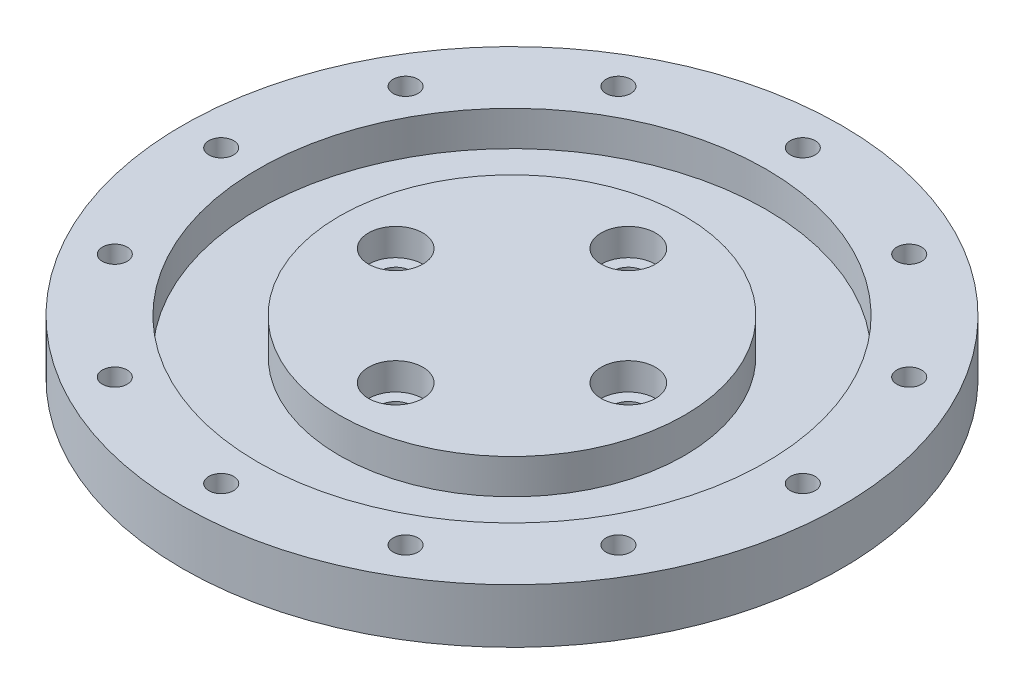
SolidWorks part; units mm, degrees
ref_plane "Ön Düzlem" through (0, 0, 0) normal (0, 0, 1) x (1, 0, 0)
ref_plane "Üst Düzlem" through (0, 0, 0) normal (0, 1, 0) x (1, 0, 0)
ref_plane "Sağ Düzlem" through (0, 0, 0) normal (1, 0, 0) x (0, 0, -1)
sketch "Sketch1" plane through (0, 0, 0) normal (0, 1, 0) x (1, 0, 0)
  circle A0 centre (0, 0) radius 42.5
  dimension "D1" = 85
extrude "Boss-Extrude1" add sketch "Sketch1" along normal blind 7
sketch "Sketch2" plane through (0, 7, 0) normal (0, 1, 0) x (1, 0, 0)
  circle A0 centre (0, 0) radius 22.25
  circle A1 centre (0, 0) radius 32.75
  dimension "D1" = 44.5
  dimension "D2" = 65.5
extrude "Cut-Extrude1" cut sketch "Sketch2" against normal blind 4.5
sketch "Sketch3" plane through (0, 7, 0) normal (0, 1, 0) x (1, 0, 0)
  circle A0 centre (0, 37.5) radius 1.6
  circle A1 centre (18.75, 32.476) radius 1.6
  circle A2 centre (32.476, 18.75) radius 1.6
  circle A3 centre (37.5, 0) radius 1.6
  circle A4 centre (32.476, -18.75) radius 1.6
  circle A5 centre (18.75, -32.476) radius 1.6
  circle A6 centre (0, -37.5) radius 1.6
  circle A7 centre (-18.75, -32.476) radius 1.6
  circle A8 centre (-32.476, -18.75) radius 1.6
  circle A9 centre (-37.5, 0) radius 1.6
  circle A10 centre (-32.476, 18.75) radius 1.6
  circle A11 centre (-18.75, 32.476) radius 1.6
  dimension "D1" = 37.5
  dimension "D2" = 12
extrude "Cut-Extrude2" cut sketch "Sketch3" against normal through all
sketch "Sketch4" plane through (0, 7, 0) normal (0, 1, 0) x (1, 0, 0)
  circle A0 centre (0, 15) radius 2
  circle A1 centre (15, 0) radius 2
  circle A2 centre (0, -15) radius 2
  circle A3 centre (-15, 0) radius 2
  dimension "D1" = 4
  dimension "D2" = 15
  dimension "D3" = 4
extrude "Cut-Extrude3" cut sketch "Sketch4" against normal through all
sketch "Sketch5" plane through (0, 7, 0) normal (0, 1, 0) x (1, 0, 0)
  circle A0 centre (0, 15) radius 2 construction
  circle A1 centre (0, 15) radius 2
  circle A2 centre (0, 15) radius 3.5
  circle A3 centre (15, 0) radius 3.5
  circle A4 centre (0, -15) radius 3.5
  circle A5 centre (-15, 0) radius 3.5
  dimension "D1" = 4
extrude "Cut-Extrude4" cut sketch "Sketch5" against normal blind 3.5
